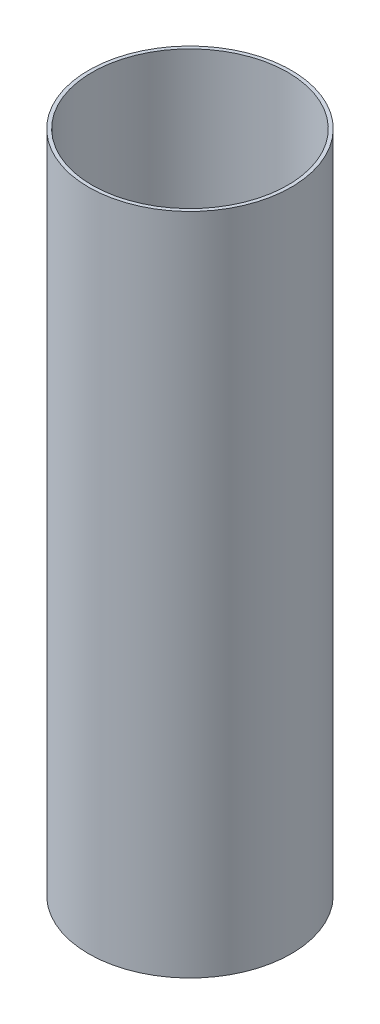
SolidWorks part; units mm, degrees
material "Acrylic (Medium-high impact)"
ref_plane "Front Plane" through (0, 0, 0) normal (0, 0, 1) x (1, 0, 0)
ref_plane "Top Plane" through (0, 0, 0) normal (0, 1, 0) x (1, 0, 0)
ref_plane "Right Plane" through (0, 0, 0) normal (1, 0, 0) x (0, 0, -1)
sketch "Sketch1" plane through (0, 0, 0) normal (0, 1, 0) x (1, 0, 0)
  circle A0 centre (0, 0) radius 92.075
  circle A1 centre (0, 0) radius 88.9
  dimension "D1" = 184.15
  dimension "D2" = 177.8
extrude "Boss-Extrude1" add sketch "Sketch1" along normal mid plane 603.25
ref_plane "Plane1" through (92.075, 0, 0) normal (1, 0, 0) x (0, 0, -1)
sketch "Sketch3" plane through (92.075, 0, 0) normal (1, 0, 0) x (0, 0, -1)
  line L0 (0, 101.2825) -> (0, -101.2825) construction
  line L1 (88.9, 301.625) -> (-88.9, 301.625) construction
  line L2 (-92.075, -301.625) -> (92.075, -301.625) construction
  circle A0 centre (0, -295.275) radius 1.4351
  circle A1 centre (0, 295.275) radius 1.4351
  dimension "D1" = 6.35
  dimension "D2" = 2.8702
  dimension "D3" = 2.8702
  dimension "D4" = 6.35
extrude "Cut-Extrude1" [suppressed] cut sketch "Sketch3" against normal blind 34.798
pattern_circular "CirPattern1" [suppressed] count 3 over 360
